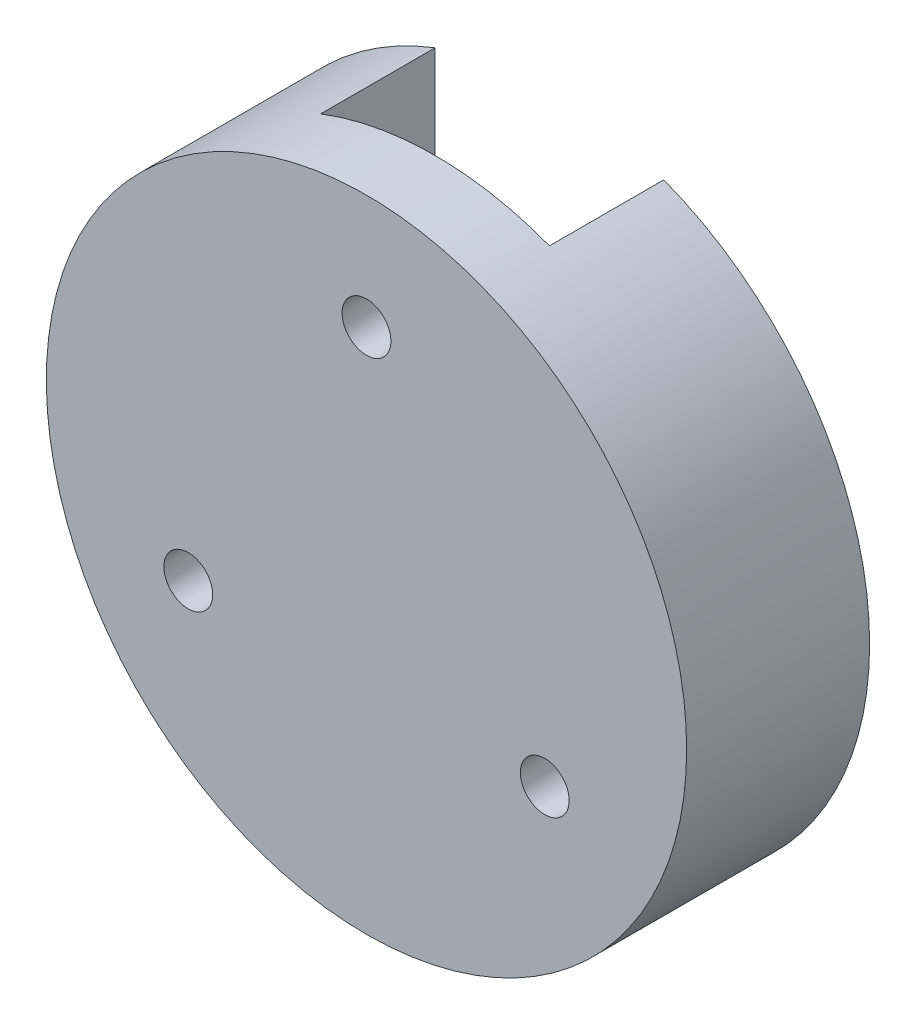
SolidWorks part; units mm, degrees
material "ABS"
ref_plane "前视基准面" through (0, 0, 0) normal (0, 0, 1) x (1, 0, 0)
ref_plane "上视基准面" through (0, 0, 0) normal (0, 1, 0) x (1, 0, 0)
ref_plane "右视基准面" through (0, 0, 0) normal (1, 0, 0) x (0, 0, -1)
sketch "草图1" plane through (0, 0, 0) normal (0, 0, 1) x (1, 0, 0)
  circle A0 centre (0, 0) radius 21
  dimension "D1" = 42
extrude "凸台-拉伸1" add sketch "草图1" along normal blind 3
sketch "草图2" plane through (0, 0, 0) normal (0, 0, -1) x (-1, 0, 0)
  circle A0 centre (0, 0) radius 21
  dimension "D1" = 42
extrude "凸台-拉伸2" add sketch "草图2" along normal blind 9
sketch "草图3" plane through (0, 0, -9) normal (0, 0, -1) x (-1, 0, 0)
  circle A0 centre (0, 0) radius 13.5 construction
  circle A1 centre (0, 13.5) radius 1.6
  circle A2 centre (11.6913, -6.75) radius 1.6
  circle A3 centre (-11.6913, -6.75) radius 1.6
  point P11 (0, 0)
  dimension "D1" = 27
  dimension "D2" = 3.2
  dimension "D3" = 3
extrude "切除-拉伸1" cut sketch "草图3" against normal blind 26.5
sketch "草图6" plane through (0, 0, -9) normal (0, 0, -1) x (-1, 0, 0)
  line L1 (-7.5, -25) -> (7.5, -25)
  line L2 (-7.5, -25) -> (-7.5, 25)
  line L3 (-7.5, 25) -> (7.5, 25)
  line L4 (7.5, -25) -> (7.5, 25)
  line L5 (-7.5, -25) -> (7.5, 25) construction
  line L6 (-7.5, 25) -> (7.5, -25) construction
  point P0 (0, 0)
  dimension "D1" = 15
  dimension "D2" = 50
extrude "切除-拉伸3" cut sketch "草图6" against normal blind 7.5
